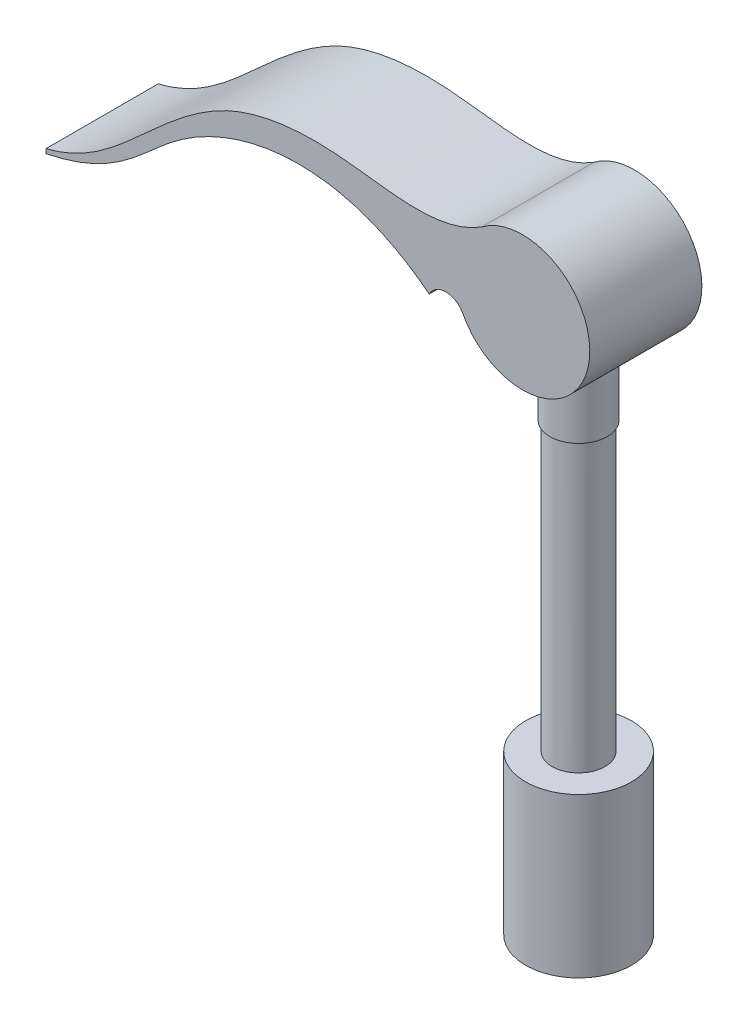
SolidWorks part; units mm, degrees
ref_plane "Front Plane" through (0, 0, 0) normal (0, 0, 1) x (1, 0, 0)
ref_plane "Top Plane" through (0, 0, 0) normal (0, 1, 0) x (1, 0, 0)
ref_plane "Right Plane" through (0, 0, 0) normal (1, 0, 0) x (0, 0, -1)
sketch "Sketch1" plane through (0, 0, 0) normal (0, 1, 0) x (1, 0, 0)
  circle A0 centre (0, 0) radius 3
  dimension "D1" = 6
extrude "Boss-Extrude1" add sketch "Sketch1" along normal mid plane 65
sketch "Sketch2" plane through (0, 0, 0) normal (0, 0, 1) x (1, 0, 0)
  line L0 (-53.975, 20.32) -> (-53.975, 20.828)
  arc A0 (-6.7669, 28.2466) -> (-4.6159, 37.8128) centre (0, 31.75) ccw
  arc A1 (-10.5769, 28.2466) -> (-6.7669, 28.2466) centre (-8.6719, 27.2603) cw
  arc A3 (-4.6159, 37.8128) -> (-6.7669, 28.2466) centre (0, 31.75) ccw construction
  spline S0 degree 3 poles (-53.975, 20.828) (-48.5791, 22.1043) (-42.7392, 28.4513) (-32.7076, 36.2172) (-19.4459, 37.6014) (-9.8051, 34.5284) (-4.6159, 37.8128) knots 0 0 0 0 0.290913 0.47228 0.684924 1 1 1 1
  spline S1 degree 3 poles (-53.975, 20.32) (-46.1217, 21.895) (-37.2728, 34.142) (-20.2627, 35.9482) (-10.5769, 28.2466) knots 0 0 0 0 0.320306 1 1 1 1
  dimension "D1" = 15.24
  dimension "D4" = 11.43
  dimension "D6" = 2.1452
  dimension "D2" = 31.75
  dimension "D3" = 53.975
  dimension "D5" = 3.81
  dimension "D7" = 0.508
  dimension "D8" = 4.6159
extrude "Boss-Extrude2" add sketch "Sketch2" along normal mid plane 12.7
sketch "Sketch3" plane through (0, 0, 0) normal (0, 1, 0) x (1, 0, 0)
  circle A0 centre (0, 0) radius 3.25
  dimension "D1" = 6.5
extrude "Boss-Extrude3" add sketch "Sketch3" along normal up to surface (6.13 mm away) from offset 18
sketch "Sketch4" plane through (0, -32.5, 0) normal (0, -1, 0) x (1, 0, 0)
  circle A0 centre (0, 0) radius 6
  dimension "D1" = 12
extrude "Boss-Extrude4" add sketch "Sketch4" against normal blind 18
